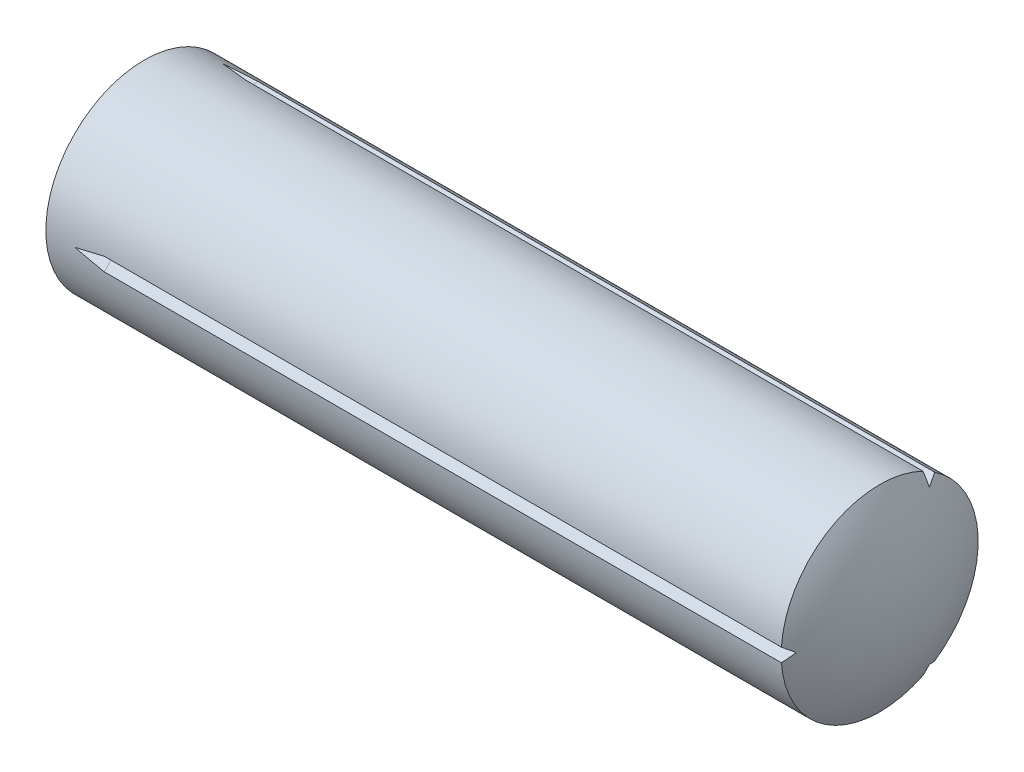
SolidWorks part; units mm, degrees
revolve "Base-Revolve" add sketch "Sketch1" angle 360 about L0
sketch "Sketch1" plane through (0, 0, 0) normal (0, 0, 1) x (1, 0, 0)
  line L0 (-117, 0) -> (21, 0) construction
  line L1 (-100, 0) -> (-100, 1.25)
  line L2 (-96.6819, 12.5) -> (-3.3494, 12.5)
  line L3 (-100, 0) -> (0, 0)
  arc A0 (-96.6819, 12.5) -> (-100, 1.25) centre (-75.0313, 0) ccw
  arc A1 (0, 0) -> (-3.3494, 12.5) centre (-25, 0) ccw
  dimension "D2" = 25
  dimension "D1" = 25
  dimension "Diameter" = 25
  dimension "Length" = 100
  dimension "D3" = 2.5
ref_plane "Plane1" through (0, 0, 0) normal (0, 0, 1) x (1, 0, 0)
ref_plane "Plane2" through (0, 0, 0) normal (0, 1, 0) x (1, 0, 0)
ref_plane "Plane3" through (0, 0, 0) normal (1, 0, 0) x (0, 0, -1)
sketch "Sketch2" plane through (0, 0, 0) normal (1, 0, 0) x (0, 0, -1)
  line L0 (0, 0) -> (-14, 0) construction
  line L1 (-11.25, 0) -> (-12.5, 0.8753)
  line L2 (-11.25, 0) -> (-12.5, -0.8753)
  line L3 (-12.5, -0.8753) -> (-12.5, 0.8753)
  circle A0 centre (0, 0) radius 11.25 construction
  circle A1 centre (0, 0) radius 12.5 construction
  dimension "D1" = 22.5
  dimension "D2" = 70
  dimension "D3" = 35
sketch "Sketch4" plane through (0, 0, 0) normal (0, 1, 0) x (1, 0, 0)
  line L0 (8, 0) -> (-110, 0) construction
  line L1 (-117, 0) -> (21, 0) construction
  line L2 (0, -11.25) -> (-89.5, -11.25)
  line L3 (-89.5, -11.25) -> (-93, -12.5)
  point P7 (-100, 0)
  dimension "D1" = 22.5
  dimension "D3" = 100
  dimension "D5" = 25
  dimension "D2" = 10.5
sweep "Cut-Sweep1" cut profiles "Sketch2" path "Sketch4"
pattern_circular "CirPattern1" count 3 over 360 about axis through (0, 0, 0) along (1, 0, 0) of "Cut-Sweep1"
equation "\"D1@Sketch1\" = \"Diameter@Sketch1\""
equation "\"D2@Sketch1\" = \"Diameter@Sketch1\""
equation "\"D1@Sketch2\" = \"Diameter@Sketch1\" * .9"
equation "\"D3@Sketch2\" = \"D2@Sketch2\" / 2"
equation "\"D1@Sketch4\" = \"D1@Sketch2\""
equation "\"D3@Sketch4\" = \"Length@Sketch1\""
equation "\"D5@Sketch4\" = \"Diameter@Sketch1\""
equation "\"D2@Sketch4\" = \"Pilot@Sketch4\" * 1.5"
equation "\"D3@Sketch1\" = \"Diameter@Sketch1\" * .1"
